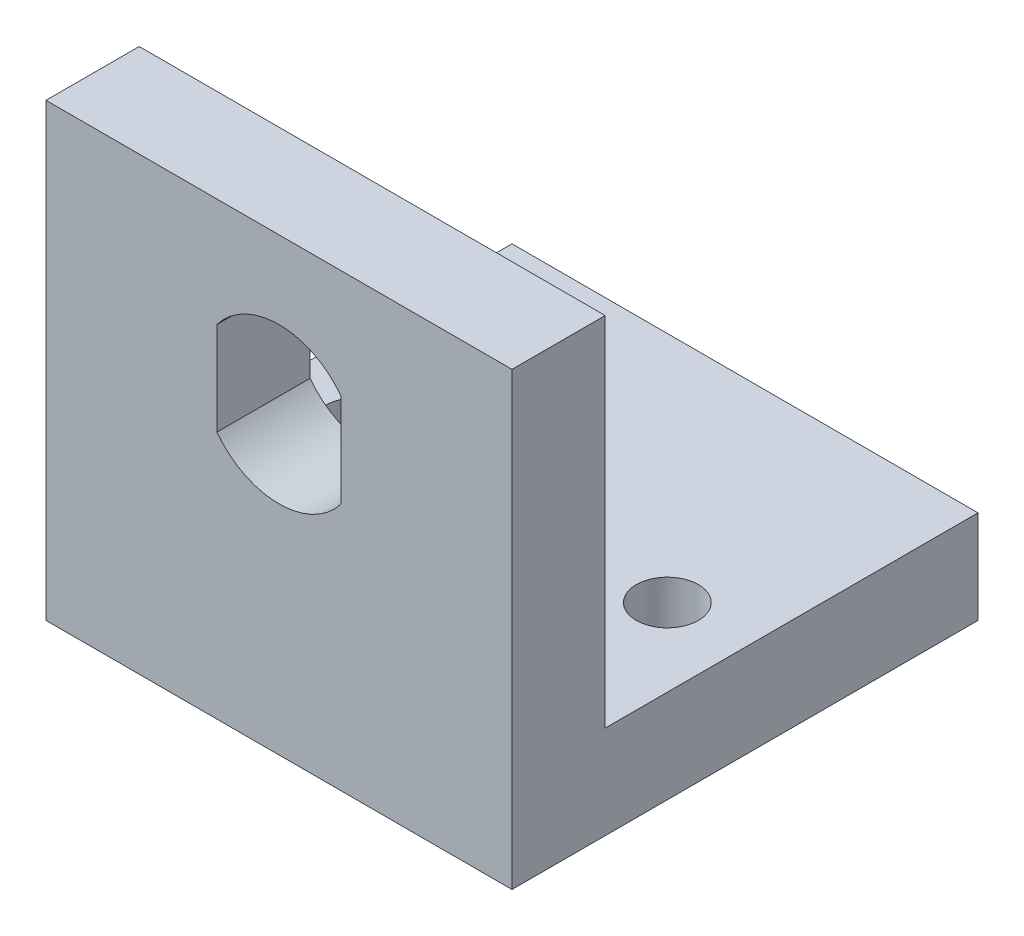
SolidWorks part; units mm, degrees
material "1060 合金"
ref_plane "前视基准面" through (0, 0, 0) normal (0, 0, 1) x (1, 0, 0)
ref_plane "上视基准面" through (0, 0, 0) normal (0, 1, 0) x (1, 0, 0)
ref_plane "右视基准面" through (0, 0, 0) normal (1, 0, 0) x (0, 0, -1)
sketch "草图1" plane through (0, 0, 0) normal (1, 0, 0) x (0, 0, -1)
  line L0 (0, 0) -> (0, 29)
  line L1 (0, 29) -> (6, 29)
  line L2 (6, 29) -> (6, 6)
  line L3 (6, 6) -> (30, 6)
  line L4 (30, 6) -> (30, 0)
  line L5 (30, 0) -> (0, 0)
  dimension "D1" = 6
  dimension "D2" = 6
  dimension "D3" = 30
  dimension "D4" = 29
extrude "凸台-拉伸1" add sketch "草图1" along normal mid plane 30
sketch "草图2" plane through (0, 0, 0) normal (0, 1, 0) x (1, 0, 0)
  line L0 (-15, 30) -> (-15, 6) construction
  line L1 (15, 30) -> (-15, 30) construction
  circle A0 centre (-10, 15) radius 2
  circle A1 centre (10, 15) radius 2
  dimension "D1" = 4
  dimension "D2" = 5
  dimension "D3" = 20
  dimension "D4" = 15
extrude "切除-拉伸1" cut sketch "草图2" along normal blind 40
sketch "草图3" plane through (0, 0, 0) normal (0, 0, 1) x (1, 0, 0)
  line L0 (15, 29) -> (-15, 29) construction
  line L1 (0, 29) -> (0, 11.1854) construction
  line L2 (-4, 22) -> (-4, 16)
  line L3 (4, 22) -> (4, 16)
  arc A0 (-4, 16) -> (4, 16) centre (0, 19) ccw
  arc A1 (4, 22) -> (-4, 22) centre (0, 19) ccw
  point P5 (0, 29)
  dimension "D1" = 10
  dimension "D2" = 10
  dimension "D3" = 4
extrude "切除-拉伸2" cut sketch "草图3" against normal blind 40
